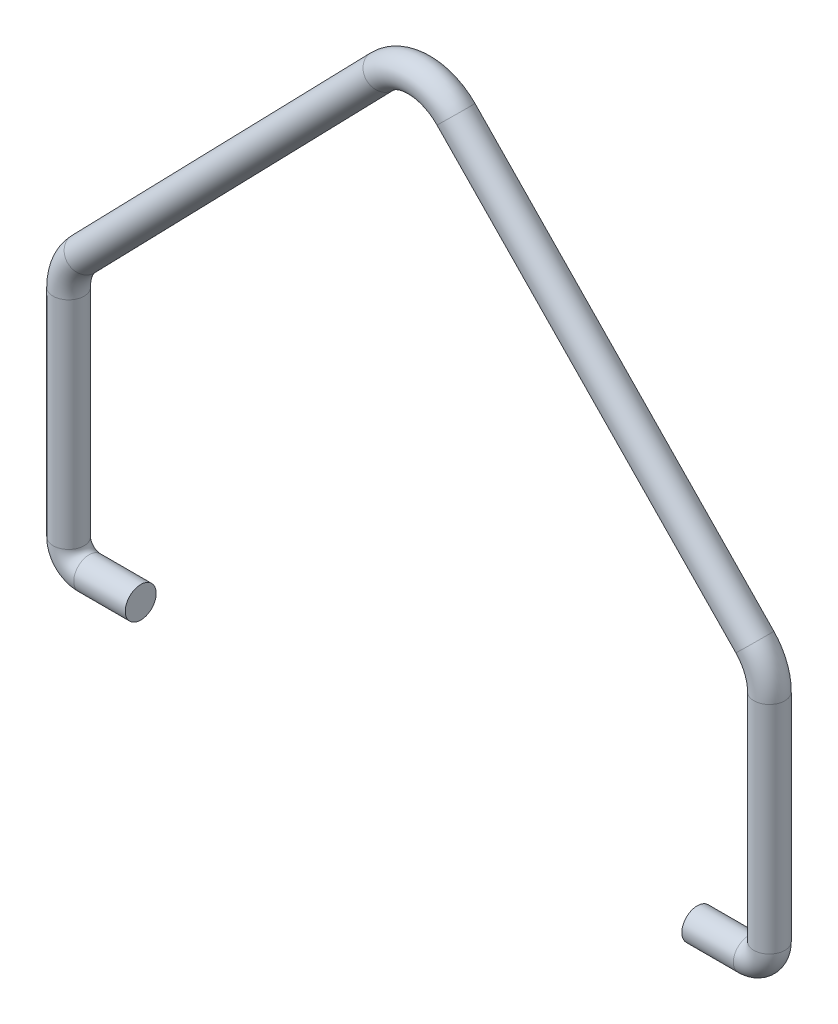
SolidWorks part; units mm, degrees
ref_plane "Front Plane" through (0, 0, 0) normal (0, 0, 1) x (1, 0, 0)
ref_plane "Top Plane" through (0, 0, 0) normal (0, 1, 0) x (1, 0, 0)
ref_plane "Right Plane" through (0, 0, 0) normal (1, 0, 0) x (0, 0, -1)
sketch "Sketch1" plane through (0, 0, 0) normal (0, 0, 1) x (1, 0, 0)
  line L0 (27, 0) -> (32, 0)
  line L1 (34, 2) -> (34, 22.9713)
  line L2 (32.5864, 26.4552) -> (3.5864, 56.3081)
  line L3 (0, 0) -> (0, 80.7459) construction
  line L4 (-27, 0) -> (-32, 0)
  line L5 (-34, 2) -> (-34, 22.9713)
  line L6 (-32.5864, 26.4552) -> (-3.5864, 56.3081)
  arc A0 (3.5864, 56.3081) -> (-3.5864, 56.3081) centre (0, 52.8242) ccw
  arc A1 (-34, 22.9713) -> (-32.5864, 26.4552) centre (-29, 22.9713) cw
  arc A2 (34, 22.9713) -> (32.5864, 26.4552) centre (29, 22.9713) ccw
  arc A3 (32, 0) -> (34, 2) centre (32, 2) ccw
  arc A4 (-32, 0) -> (-34, 2) centre (-32, 2) cw
  point P12 (0, 60)
  point P16 (-34, 25)
  point P19 (34, 25)
  point P22 (34, 0)
  point P25 (-34, 0)
  dimension "D3" = 5
  dimension "D4" = 2
  dimension "D1" = 25
  dimension "D2" = 60
  dimension "D5" = 34
  dimension "D6" = 7
sweep "Sweep2" add path "Sketch1" circular profile diameter 3 parameters "D3"=3
